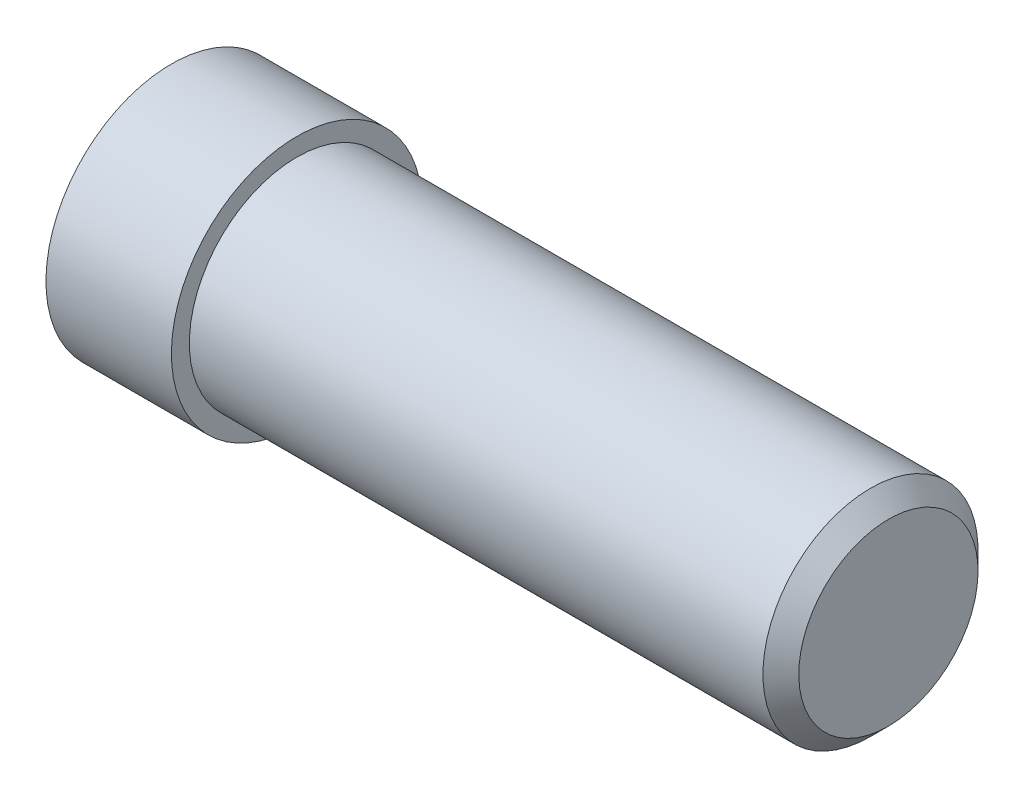
SolidWorks part; units mm, degrees
material "AISI 4340 Çelik, tavlı"
ref_plane "Ön Düzlem" through (0, 0, 0) normal (0, 0, 1) x (1, 0, 0)
ref_plane "Üst Düzlem" through (0, 0, 0) normal (0, 1, 0) x (1, 0, 0)
ref_plane "Sağ Düzlem" through (0, 0, 0) normal (1, 0, 0) x (0, 0, -1)
sketch "Çizim1" plane through (0, 0, 0) normal (0, 0, 1) x (1, 0, 0)
  line L0 (0, 0) -> (0, 6)
  line L1 (0, 6) -> (-33, 6)
  line L2 (-33, 6) -> (-33, 7)
  line L3 (-33, 7) -> (-40, 7)
  line L4 (-40, 7) -> (-40, 0)
  line L5 (-40, 0) -> (0, 0)
  dimension "D1" = 7
  dimension "D2" = 7
  dimension "D3" = 6
  dimension "D4" = 1
  dimension "D5" = 33
revolve "Döndür1" add sketch "Çizim1" angle 360 about L5
chamfer "Pah1" distance 1 angle 45 1 edges at (0, -6, 0)
